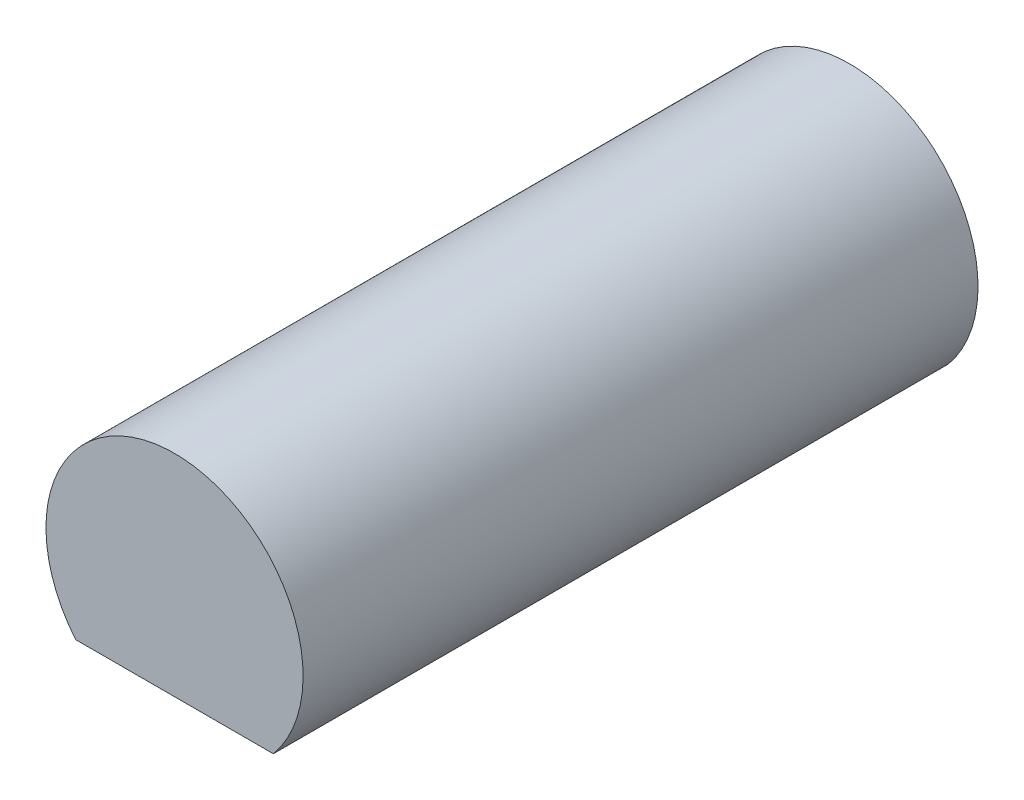
SolidWorks part; units mm, degrees
material "Malleable Cast Iron"
ref_plane "Front Plane" through (0, 0, 0) normal (0, 0, 1) x (1, 0, 0)
ref_plane "Top Plane" through (0, 0, 0) normal (0, 1, 0) x (1, 0, 0)
ref_plane "Right Plane" through (0, 0, 0) normal (1, 0, 0) x (0, 0, -1)
sketch "Sketch1" plane through (0, 0, 0) normal (0, 0, 1) x (1, 0, 0)
  line L0 (3.075, -2.5582) -> (-3.075, -2.5582)
  arc A0 (3.075, -2.5582) -> (-3.075, -2.5582) centre (0, 0) ccw
  dimension "D1" = 8
  dimension "D2" = 6.15
extrude "Boss-Extrude1" add sketch "Sketch1" along normal mid plane 21
